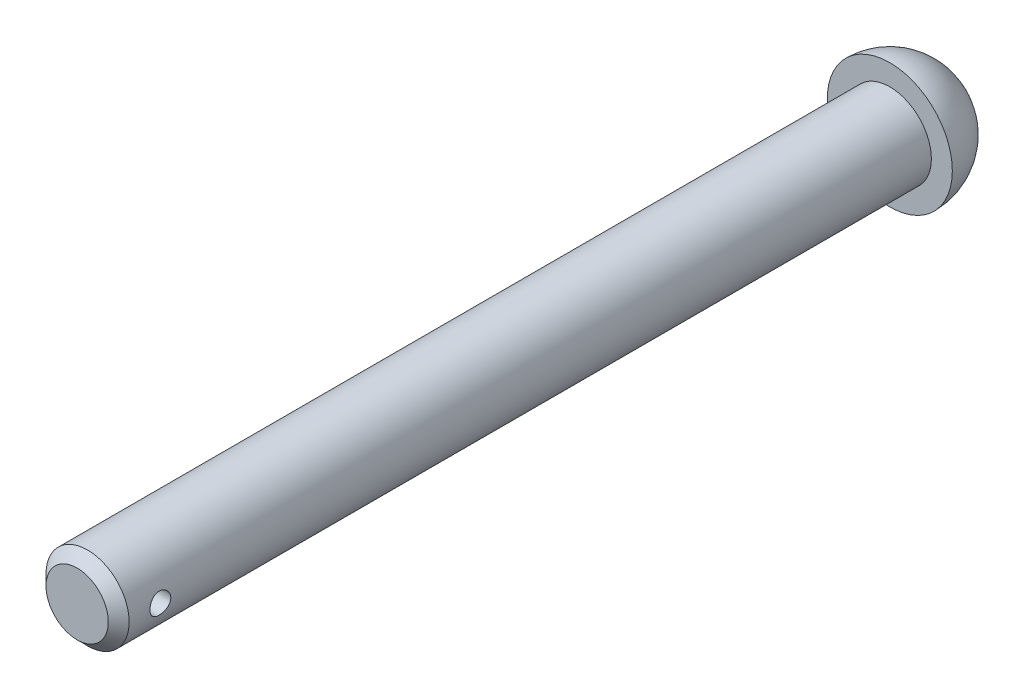
SolidWorks part; units mm, degrees
ref_plane "Front Plane" through (0, 0, 0) normal (0, 0, 1) x (1, 0, 0)
ref_plane "Top Plane" through (0, 0, 0) normal (0, 1, 0) x (1, 0, 0)
ref_plane "Right Plane" through (0, 0, 0) normal (1, 0, 0) x (0, 0, -1)
sketch "Sketch1" plane through (0, 0, 0) normal (1, 0, 0) x (0, 0, -1)
  line L0 (0, 1.9946) -> (39, 1.9946)
  line L1 (39, 1.9946) -> (39, 3)
  line L2 (0, 1.9946) -> (0, 0)
  line L3 (0, 0) -> (42, 0)
  arc A0 (39, 3) -> (42, 0) centre (39, 0) cw
  dimension "D1" = 3
  dimension "D2" = 39
revolve "Revolve1" add sketch "Sketch1" angle 360 about L3
sketch "Sketch2" plane through (0, 0, 0) normal (1, 0, 0) x (0, 0, -1)
  line L0 (39, 1.9946) -> (39, -1.9946) construction
  circle A0 centre (2, 0) radius 0.5
  dimension "D1" = 1
  dimension "D2" = 37
extrude "Cut-Extrude1" cut sketch "Sketch2" against normal mid plane 10
chamfer "Chamfer1" distance 0.5 angle 45 1 edges at (1.9946, 0, 0)
